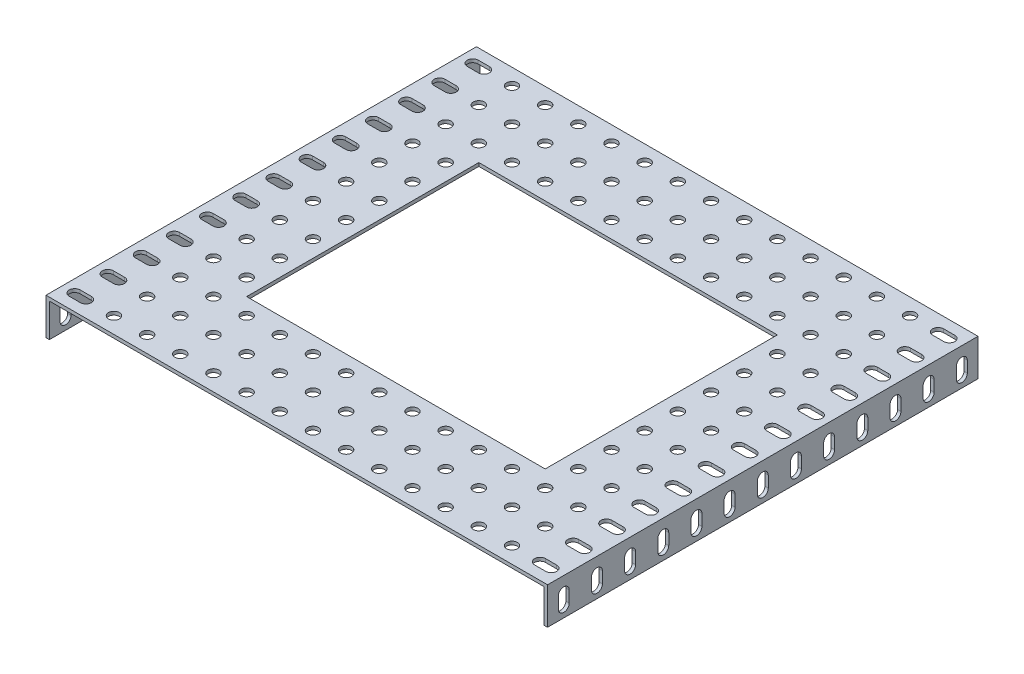
SolidWorks part; units mm, degrees
ref_plane "Front Plane" through (0, 0, 0) normal (0, 0, 1) x (1, 0, 0)
ref_plane "Top Plane" through (0, 0, 0) normal (0, 1, 0) x (1, 0, 0)
ref_plane "Right Plane" through (0, 0, 0) normal (1, 0, 0) x (0, 0, -1)
sketch "Sketch1" plane through (0, 0, 0) normal (0, 1, 0) x (1, 0, 0)
  line L0 (0, -76.56) -> (0, 76.56) construction
  line L1 (-91.66, 76.56) -> (-87.36, 76.56) construction
  line L2 (-91.66, 78.67) -> (-87.36, 78.67)
  line L3 (-91.66, 74.45) -> (-87.36, 74.45)
  line L4 (-91.66, 63.8) -> (-87.36, 63.8) construction
  line L5 (-91.66, 65.91) -> (-87.36, 65.91)
  line L6 (-91.66, 61.69) -> (-87.36, 61.69)
  line L7 (-91.66, 51.04) -> (-87.36, 51.04) construction
  line L8 (-91.66, 53.15) -> (-87.36, 53.15)
  line L9 (-91.66, 48.93) -> (-87.36, 48.93)
  line L10 (-91.66, 38.28) -> (-87.36, 38.28) construction
  line L11 (-91.66, 40.39) -> (-87.36, 40.39)
  line L12 (-91.66, 36.17) -> (-87.36, 36.17)
  line L13 (-91.66, 25.52) -> (-87.36, 25.52) construction
  line L14 (-91.66, 27.63) -> (-87.36, 27.63)
  line L15 (-91.66, 23.41) -> (-87.36, 23.41)
  line L16 (-91.66, 12.76) -> (-87.36, 12.76) construction
  line L17 (-91.66, 14.87) -> (-87.36, 14.87)
  line L18 (-91.66, 10.65) -> (-87.36, 10.65)
  line L19 (-91.66, 0) -> (-87.36, 0) construction
  line L20 (-91.66, 2.11) -> (-87.36, 2.11)
  line L21 (-91.66, -2.11) -> (-87.36, -2.11)
  line L22 (-91.66, -12.76) -> (-87.36, -12.76) construction
  line L23 (-91.66, -10.65) -> (-87.36, -10.65)
  line L24 (-91.66, -14.87) -> (-87.36, -14.87)
  line L25 (-91.66, -25.52) -> (-87.36, -25.52) construction
  line L26 (-91.66, -23.41) -> (-87.36, -23.41)
  line L27 (-91.66, -27.63) -> (-87.36, -27.63)
  line L28 (-91.66, -38.28) -> (-87.36, -38.28) construction
  line L29 (-91.66, -36.17) -> (-87.36, -36.17)
  line L30 (-91.66, -40.39) -> (-87.36, -40.39)
  line L31 (-91.66, -51.04) -> (-87.36, -51.04) construction
  line L32 (-91.66, -48.93) -> (-87.36, -48.93)
  line L33 (-91.66, -53.15) -> (-87.36, -53.15)
  line L34 (-91.66, -63.8) -> (-87.36, -63.8) construction
  line L35 (-91.66, -61.69) -> (-87.36, -61.69)
  line L36 (-91.66, -65.91) -> (-87.36, -65.91)
  line L37 (-91.66, -76.56) -> (-87.36, -76.56) construction
  line L38 (-91.66, -74.45) -> (-87.36, -74.45)
  line L39 (-91.66, -78.67) -> (-87.36, -78.67)
  line L40 (91.66, 76.56) -> (87.36, 76.56) construction
  line L41 (91.66, 78.67) -> (87.36, 78.67)
  line L42 (91.66, 74.45) -> (87.36, 74.45)
  line L43 (91.66, 63.8) -> (87.36, 63.8) construction
  line L44 (91.66, 65.91) -> (87.36, 65.91)
  line L45 (91.66, 61.69) -> (87.36, 61.69)
  line L46 (91.66, 51.04) -> (87.36, 51.04) construction
  line L47 (91.66, 53.15) -> (87.36, 53.15)
  line L48 (91.66, 48.93) -> (87.36, 48.93)
  line L49 (91.66, 38.28) -> (87.36, 38.28) construction
  line L50 (91.66, 40.39) -> (87.36, 40.39)
  line L51 (91.66, 36.17) -> (87.36, 36.17)
  line L52 (91.66, 25.52) -> (87.36, 25.52) construction
  line L53 (91.66, 27.63) -> (87.36, 27.63)
  line L54 (91.66, 23.41) -> (87.36, 23.41)
  line L55 (91.66, 12.76) -> (87.36, 12.76) construction
  line L56 (91.66, 14.87) -> (87.36, 14.87)
  line L57 (91.66, 10.65) -> (87.36, 10.65)
  line L58 (91.66, 0) -> (87.36, 0) construction
  line L59 (91.66, 2.11) -> (87.36, 2.11)
  line L60 (91.66, -2.11) -> (87.36, -2.11)
  line L61 (91.66, -12.76) -> (87.36, -12.76) construction
  line L62 (91.66, -10.65) -> (87.36, -10.65)
  line L63 (91.66, -14.87) -> (87.36, -14.87)
  line L64 (91.66, -25.52) -> (87.36, -25.52) construction
  line L65 (91.66, -23.41) -> (87.36, -23.41)
  line L66 (91.66, -27.63) -> (87.36, -27.63)
  line L67 (91.66, -38.28) -> (87.36, -38.28) construction
  line L68 (91.66, -36.17) -> (87.36, -36.17)
  line L69 (91.66, -40.39) -> (87.36, -40.39)
  line L70 (91.66, -51.04) -> (87.36, -51.04) construction
  line L71 (91.66, -48.93) -> (87.36, -48.93)
  line L72 (91.66, -53.15) -> (87.36, -53.15)
  line L73 (91.66, -63.8) -> (87.36, -63.8) construction
  line L74 (91.66, -61.69) -> (87.36, -61.69)
  line L75 (91.66, -65.91) -> (87.36, -65.91)
  line L76 (91.66, -76.56) -> (87.36, -76.56) construction
  line L77 (91.66, -74.45) -> (87.36, -74.45)
  line L78 (91.66, -78.67) -> (87.36, -78.67)
  line L80 (-93.77, 51.04) -> (-96.47, 51.04) construction
  line L81 (-96.47, 51.04) -> (-96.47, 82.79) construction
  line L83 (91.66, -78.67) -> (91.66, -82.79) construction
  line L84 (91.66, -82.79) -> (96.47, -82.79) construction
  line L86 (-96.47, 82.79) -> (96.47, 82.79)
  line L87 (-96.47, 82.79) -> (-96.47, -82.79)
  line L88 (-96.47, -82.79) -> (96.47, -82.79)
  line L89 (96.47, 82.79) -> (96.47, -82.79)
  circle A0 centre (-76.56, -76.56) radius 2.11
  circle A1 centre (-63.8, -76.56) radius 2.11
  circle A2 centre (-51.04, -76.56) radius 2.11
  circle A3 centre (-38.28, -76.56) radius 2.11
  circle A4 centre (-25.52, -76.56) radius 2.11
  circle A5 centre (-12.76, -76.56) radius 2.11
  circle A6 centre (0, -76.56) radius 2.11
  circle A7 centre (12.76, -76.56) radius 2.11
  circle A8 centre (25.52, -76.56) radius 2.11
  circle A9 centre (38.28, -76.56) radius 2.11
  circle A10 centre (51.04, -76.56) radius 2.11
  circle A11 centre (63.8, -76.56) radius 2.11
  circle A12 centre (76.56, -76.56) radius 2.11
  circle A13 centre (-63.8, -63.8) radius 2.11
  circle A14 centre (-51.04, -63.8) radius 2.11
  circle A15 centre (-38.28, -63.8) radius 2.11
  circle A16 centre (-25.52, -63.8) radius 2.11
  circle A17 centre (-12.76, -63.8) radius 2.11
  circle A18 centre (0, -63.8) radius 2.11
  circle A19 centre (12.76, -63.8) radius 2.11
  circle A20 centre (25.52, -63.8) radius 2.11
  circle A21 centre (38.28, -63.8) radius 2.11
  circle A22 centre (51.04, -63.8) radius 2.11
  circle A23 centre (63.8, -63.8) radius 2.11
  circle A24 centre (76.56, -63.8) radius 2.11
  circle A25 centre (-63.8, -51.04) radius 2.11
  circle A26 centre (-51.04, -51.04) radius 2.11
  circle A27 centre (-38.28, -51.04) radius 2.11
  circle A28 centre (-25.52, -51.04) radius 2.11
  circle A29 centre (-12.76, -51.04) radius 2.11
  circle A30 centre (0, -51.04) radius 2.11
  circle A31 centre (12.76, -51.04) radius 2.11
  circle A32 centre (25.52, -51.04) radius 2.11
  circle A33 centre (38.28, -51.04) radius 2.11
  circle A34 centre (51.04, -51.04) radius 2.11
  circle A35 centre (63.8, -51.04) radius 2.11
  circle A36 centre (76.56, -51.04) radius 2.11
  circle A37 centre (-63.8, -38.28) radius 2.11
  circle A38 centre (-51.04, -38.28) radius 2.11
  circle A39 centre (-38.28, -38.28) radius 2.11
  circle A40 centre (-25.52, -38.28) radius 2.11
  circle A41 centre (-12.76, -38.28) radius 2.11
  circle A42 centre (0, -38.28) radius 2.11
  circle A43 centre (12.76, -38.28) radius 2.11
  circle A44 centre (25.52, -38.28) radius 2.11
  circle A45 centre (38.28, -38.28) radius 2.11
  circle A46 centre (51.04, -38.28) radius 2.11
  circle A47 centre (63.8, -38.28) radius 2.11
  circle A48 centre (76.56, -38.28) radius 2.11
  circle A49 centre (-63.8, -25.52) radius 2.11
  circle A50 centre (-51.04, -25.52) radius 2.11
  circle A51 centre (-38.28, -25.52) radius 2.11
  circle A52 centre (-25.52, -25.52) radius 2.11
  circle A53 centre (-12.76, -25.52) radius 2.11
  circle A54 centre (0, -25.52) radius 2.11
  circle A55 centre (12.76, -25.52) radius 2.11
  circle A56 centre (25.52, -25.52) radius 2.11
  circle A57 centre (38.28, -25.52) radius 2.11
  circle A58 centre (51.04, -25.52) radius 2.11
  circle A59 centre (63.8, -25.52) radius 2.11
  circle A60 centre (76.56, -25.52) radius 2.11
  circle A61 centre (-63.8, -12.76) radius 2.11
  circle A62 centre (-51.04, -12.76) radius 2.11
  circle A63 centre (-38.28, -12.76) radius 2.11
  circle A64 centre (-25.52, -12.76) radius 2.11
  circle A65 centre (-12.76, -12.76) radius 2.11
  circle A66 centre (0, -12.76) radius 2.11
  circle A67 centre (12.76, -12.76) radius 2.11
  circle A68 centre (25.52, -12.76) radius 2.11
  circle A69 centre (38.28, -12.76) radius 2.11
  circle A70 centre (51.04, -12.76) radius 2.11
  circle A71 centre (63.8, -12.76) radius 2.11
  circle A72 centre (76.56, -12.76) radius 2.11
  circle A73 centre (-63.8, 0) radius 2.11
  circle A74 centre (-51.04, 0) radius 2.11
  circle A75 centre (-38.28, 0) radius 2.11
  circle A76 centre (-25.52, 0) radius 2.11
  circle A77 centre (-12.76, 0) radius 2.11
  circle A78 centre (0, 0) radius 2.11
  circle A79 centre (12.76, 0) radius 2.11
  circle A80 centre (25.52, 0) radius 2.11
  circle A81 centre (38.28, 0) radius 2.11
  circle A82 centre (51.04, 0) radius 2.11
  circle A83 centre (63.8, 0) radius 2.11
  circle A84 centre (76.56, 0) radius 2.11
  circle A85 centre (-63.8, 12.76) radius 2.11
  circle A86 centre (-51.04, 12.76) radius 2.11
  circle A87 centre (-38.28, 12.76) radius 2.11
  circle A88 centre (-25.52, 12.76) radius 2.11
  circle A89 centre (-12.76, 12.76) radius 2.11
  circle A90 centre (0, 12.76) radius 2.11
  circle A91 centre (12.76, 12.76) radius 2.11
  circle A92 centre (25.52, 12.76) radius 2.11
  circle A93 centre (38.28, 12.76) radius 2.11
  circle A94 centre (51.04, 12.76) radius 2.11
  circle A95 centre (63.8, 12.76) radius 2.11
  circle A96 centre (76.56, 12.76) radius 2.11
  circle A97 centre (-63.8, 25.52) radius 2.11
  circle A98 centre (-51.04, 25.52) radius 2.11
  circle A99 centre (-38.28, 25.52) radius 2.11
  circle A100 centre (-25.52, 25.52) radius 2.11
  circle A101 centre (-12.76, 25.52) radius 2.11
  circle A102 centre (0, 25.52) radius 2.11
  circle A103 centre (12.76, 25.52) radius 2.11
  circle A104 centre (25.52, 25.52) radius 2.11
  circle A105 centre (38.28, 25.52) radius 2.11
  circle A106 centre (51.04, 25.52) radius 2.11
  circle A107 centre (63.8, 25.52) radius 2.11
  circle A108 centre (76.56, 25.52) radius 2.11
  circle A109 centre (-63.8, 38.28) radius 2.11
  circle A110 centre (-51.04, 38.28) radius 2.11
  circle A111 centre (-38.28, 38.28) radius 2.11
  circle A112 centre (-25.52, 38.28) radius 2.11
  circle A113 centre (-12.76, 38.28) radius 2.11
  circle A114 centre (0, 38.28) radius 2.11
  circle A115 centre (12.76, 38.28) radius 2.11
  circle A116 centre (25.52, 38.28) radius 2.11
  circle A117 centre (38.28, 38.28) radius 2.11
  circle A118 centre (51.04, 38.28) radius 2.11
  circle A119 centre (63.8, 38.28) radius 2.11
  circle A120 centre (76.56, 38.28) radius 2.11
  circle A121 centre (-63.8, 51.04) radius 2.11
  circle A122 centre (-51.04, 51.04) radius 2.11
  circle A123 centre (-38.28, 51.04) radius 2.11
  circle A124 centre (-25.52, 51.04) radius 2.11
  circle A125 centre (-12.76, 51.04) radius 2.11
  circle A126 centre (0, 51.04) radius 2.11
  circle A127 centre (12.76, 51.04) radius 2.11
  circle A128 centre (25.52, 51.04) radius 2.11
  circle A129 centre (38.28, 51.04) radius 2.11
  circle A130 centre (51.04, 51.04) radius 2.11
  circle A131 centre (63.8, 51.04) radius 2.11
  circle A132 centre (76.56, 51.04) radius 2.11
  circle A133 centre (-63.8, 63.8) radius 2.11
  circle A134 centre (-51.04, 63.8) radius 2.11
  circle A135 centre (-38.28, 63.8) radius 2.11
  circle A136 centre (-25.52, 63.8) radius 2.11
  circle A137 centre (-12.76, 63.8) radius 2.11
  circle A138 centre (0, 63.8) radius 2.11
  circle A139 centre (12.76, 63.8) radius 2.11
  circle A140 centre (25.52, 63.8) radius 2.11
  circle A141 centre (38.28, 63.8) radius 2.11
  circle A142 centre (51.04, 63.8) radius 2.11
  circle A143 centre (63.8, 63.8) radius 2.11
  circle A144 centre (76.56, 63.8) radius 2.11
  circle A145 centre (-63.8, 76.56) radius 2.11
  circle A146 centre (-51.04, 76.56) radius 2.11
  circle A147 centre (-38.28, 76.56) radius 2.11
  circle A148 centre (-25.52, 76.56) radius 2.11
  circle A149 centre (-12.76, 76.56) radius 2.11
  circle A150 centre (0, 76.56) radius 2.11
  circle A151 centre (12.76, 76.56) radius 2.11
  circle A152 centre (25.52, 76.56) radius 2.11
  circle A153 centre (38.28, 76.56) radius 2.11
  circle A154 centre (51.04, 76.56) radius 2.11
  circle A155 centre (63.8, 76.56) radius 2.11
  circle A156 centre (76.56, 76.56) radius 2.11
  circle A157 centre (-76.56, -63.8) radius 2.11
  circle A158 centre (-76.56, -51.04) radius 2.11
  circle A159 centre (-76.56, -38.28) radius 2.11
  circle A160 centre (-76.56, -25.52) radius 2.11
  circle A161 centre (-76.56, -12.76) radius 2.11
  circle A162 centre (-76.56, 0) radius 2.11
  circle A163 centre (-76.56, 12.76) radius 2.11
  circle A164 centre (-76.56, 25.52) radius 2.11
  circle A165 centre (-76.56, 38.28) radius 2.11
  circle A166 centre (-76.56, 51.04) radius 2.11
  circle A167 centre (-76.56, 63.8) radius 2.11
  circle A168 centre (-76.56, 76.56) radius 2.11
  arc A169 (-91.66, 78.67) -> (-91.66, 74.45) centre (-91.66, 76.56) ccw
  arc A170 (-87.36, 74.45) -> (-87.36, 78.67) centre (-87.36, 76.56) ccw
  arc A171 (-91.66, 65.91) -> (-91.66, 61.69) centre (-91.66, 63.8) ccw
  arc A172 (-87.36, 61.69) -> (-87.36, 65.91) centre (-87.36, 63.8) ccw
  arc A173 (-91.66, 53.15) -> (-91.66, 48.93) centre (-91.66, 51.04) ccw
  arc A174 (-87.36, 48.93) -> (-87.36, 53.15) centre (-87.36, 51.04) ccw
  arc A175 (-91.66, 40.39) -> (-91.66, 36.17) centre (-91.66, 38.28) ccw
  arc A176 (-87.36, 36.17) -> (-87.36, 40.39) centre (-87.36, 38.28) ccw
  arc A177 (-91.66, 27.63) -> (-91.66, 23.41) centre (-91.66, 25.52) ccw
  arc A178 (-87.36, 23.41) -> (-87.36, 27.63) centre (-87.36, 25.52) ccw
  arc A179 (-91.66, 14.87) -> (-91.66, 10.65) centre (-91.66, 12.76) ccw
  arc A180 (-87.36, 10.65) -> (-87.36, 14.87) centre (-87.36, 12.76) ccw
  arc A181 (-91.66, 2.11) -> (-91.66, -2.11) centre (-91.66, 0) ccw
  arc A182 (-87.36, -2.11) -> (-87.36, 2.11) centre (-87.36, 0) ccw
  arc A183 (-91.66, -10.65) -> (-91.66, -14.87) centre (-91.66, -12.76) ccw
  arc A184 (-87.36, -14.87) -> (-87.36, -10.65) centre (-87.36, -12.76) ccw
  arc A185 (-91.66, -23.41) -> (-91.66, -27.63) centre (-91.66, -25.52) ccw
  arc A186 (-87.36, -27.63) -> (-87.36, -23.41) centre (-87.36, -25.52) ccw
  arc A187 (-91.66, -36.17) -> (-91.66, -40.39) centre (-91.66, -38.28) ccw
  arc A188 (-87.36, -40.39) -> (-87.36, -36.17) centre (-87.36, -38.28) ccw
  arc A189 (-91.66, -48.93) -> (-91.66, -53.15) centre (-91.66, -51.04) ccw
  arc A190 (-87.36, -53.15) -> (-87.36, -48.93) centre (-87.36, -51.04) ccw
  arc A191 (-91.66, -61.69) -> (-91.66, -65.91) centre (-91.66, -63.8) ccw
  arc A192 (-87.36, -65.91) -> (-87.36, -61.69) centre (-87.36, -63.8) ccw
  arc A193 (-91.66, -74.45) -> (-91.66, -78.67) centre (-91.66, -76.56) ccw
  arc A194 (-87.36, -78.67) -> (-87.36, -74.45) centre (-87.36, -76.56) ccw
  arc A195 (91.66, 78.67) -> (91.66, 74.45) centre (91.66, 76.56) cw
  arc A196 (87.36, 74.45) -> (87.36, 78.67) centre (87.36, 76.56) cw
  arc A197 (91.66, 65.91) -> (91.66, 61.69) centre (91.66, 63.8) cw
  arc A198 (87.36, 61.69) -> (87.36, 65.91) centre (87.36, 63.8) cw
  arc A199 (91.66, 53.15) -> (91.66, 48.93) centre (91.66, 51.04) cw
  arc A200 (87.36, 48.93) -> (87.36, 53.15) centre (87.36, 51.04) cw
  arc A201 (91.66, 40.39) -> (91.66, 36.17) centre (91.66, 38.28) cw
  arc A202 (87.36, 36.17) -> (87.36, 40.39) centre (87.36, 38.28) cw
  arc A203 (91.66, 27.63) -> (91.66, 23.41) centre (91.66, 25.52) cw
  arc A204 (87.36, 23.41) -> (87.36, 27.63) centre (87.36, 25.52) cw
  arc A205 (91.66, 14.87) -> (91.66, 10.65) centre (91.66, 12.76) cw
  arc A206 (87.36, 10.65) -> (87.36, 14.87) centre (87.36, 12.76) cw
  arc A207 (91.66, 2.11) -> (91.66, -2.11) centre (91.66, 0) cw
  arc A208 (87.36, -2.11) -> (87.36, 2.11) centre (87.36, 0) cw
  arc A209 (91.66, -10.65) -> (91.66, -14.87) centre (91.66, -12.76) cw
  arc A210 (87.36, -14.87) -> (87.36, -10.65) centre (87.36, -12.76) cw
  arc A211 (91.66, -23.41) -> (91.66, -27.63) centre (91.66, -25.52) cw
  arc A212 (87.36, -27.63) -> (87.36, -23.41) centre (87.36, -25.52) cw
  arc A213 (91.66, -36.17) -> (91.66, -40.39) centre (91.66, -38.28) cw
  arc A214 (87.36, -40.39) -> (87.36, -36.17) centre (87.36, -38.28) cw
  arc A215 (91.66, -48.93) -> (91.66, -53.15) centre (91.66, -51.04) cw
  arc A216 (87.36, -53.15) -> (87.36, -48.93) centre (87.36, -51.04) cw
  arc A217 (91.66, -61.69) -> (91.66, -65.91) centre (91.66, -63.8) cw
  arc A218 (87.36, -65.91) -> (87.36, -61.69) centre (87.36, -63.8) cw
  arc A219 (91.66, -74.45) -> (91.66, -78.67) centre (91.66, -76.56) cw
  arc A220 (87.36, -78.67) -> (87.36, -74.45) centre (87.36, -76.56) cw
  point P2 (-78.67, 76.56)
  point P3 (-89.51, 76.56)
  point P347 (-85.25, 76.56)
  point P348 (-2.11, 76.56)
  point P349 (-12.76, 74.45)
  point P350 (-89.51, 63.8)
  point P351 (-93.77, 76.56)
  point P358 (-89.51, 51.04)
  point P365 (-89.51, 38.28)
  point P372 (-89.51, 25.52)
  point P379 (-89.51, 12.76)
  point P386 (-89.51, 0)
  point P393 (-89.51, -12.76)
  point P400 (-89.51, -25.52)
  point P407 (-89.51, -38.28)
  point P414 (-89.51, -51.04)
  point P421 (-89.51, -63.8)
  point P428 (-89.51, -76.56)
  point P436 (-12.76, 65.91)
  point P437 (-10.65, 76.56)
  point P439 (89.51, 76.56)
  point P446 (89.51, 63.8)
  point P453 (89.51, 51.04)
  point P460 (89.51, 38.28)
  point P467 (89.51, 25.52)
  point P474 (89.51, 12.76)
  point P481 (89.51, 0)
  point P488 (89.51, -12.76)
  point P495 (89.51, -25.52)
  point P502 (89.51, -38.28)
  point P509 (89.51, -51.04)
  point P516 (89.51, -63.8)
  point P523 (89.51, -76.56)
  point P528 (93.77, 76.56)
  point P529 (85.25, 76.56)
  point P530 (-63.8, 78.67)
  point P533 (-93.77, 51.04)
  point P536 (93.77, -76.56)
  dimension "D1" = 4.22
  dimension "D4" = 6.58
  dimension "D5" = 4.22
  dimension "D6" = 8.52
  dimension "D7" = 8.54
  dimension "D9" = 8.54
  dimension "D10" = 8.54
  dimension "D11" = 4.12
  dimension "D12" = 2.7
  dimension "D13" = 2.7
  dimension "D14" = 4.12
  dimension "D2" = 13
  dimension "D3" = 13
  dimension "D8" = 13
extrude "Boss-Extrude1" add sketch "Sketch1" against normal blind 1.3
sketch "Sketch3" plane through (-96.47, 0, 0) normal (-1, 0, 0) x (0, 0, 1)
  line L0 (-76.56, -1.3) -> (-76.56, -14.16) construction
  line L1 (-82.79, 0) -> (82.79, 0)
  line L2 (-82.79, 0) -> (-82.79, -14.16)
  line L3 (-82.79, -14.16) -> (82.79, -14.16)
  line L4 (82.79, 0) -> (82.79, -14.16)
  line L5 (-76.56, -5.91) -> (-76.56, -10.21) construction
  line L6 (-74.45, -5.91) -> (-74.45, -10.21)
  line L7 (-78.67, -5.91) -> (-78.67, -10.21)
  line L11 (-82.79, -1.3) -> (82.79, -1.3) construction
  line L17 (-74.45, 0) -> (-78.67, 0) construction
  line L20 (-63.8, -5.91) -> (-63.8, -10.21) construction
  line L23 (-61.69, -5.91) -> (-61.69, -10.21)
  line L26 (-65.91, -5.91) -> (-65.91, -10.21)
  line L29 (-51.04, -5.91) -> (-51.04, -10.21) construction
  line L32 (-48.93, -5.91) -> (-48.93, -10.21)
  line L35 (-53.15, -5.91) -> (-53.15, -10.21)
  line L38 (-38.28, -5.91) -> (-38.28, -10.21) construction
  line L41 (-36.17, -5.91) -> (-36.17, -10.21)
  line L44 (-40.39, -5.91) -> (-40.39, -10.21)
  line L47 (-25.52, -5.91) -> (-25.52, -10.21) construction
  line L50 (-23.41, -5.91) -> (-23.41, -10.21)
  line L53 (-27.63, -5.91) -> (-27.63, -10.21)
  line L54 (-12.76, -5.91) -> (-12.76, -10.21) construction
  line L55 (-10.65, -5.91) -> (-10.65, -10.21)
  line L56 (-14.87, -5.91) -> (-14.87, -10.21)
  line L57 (0, -5.91) -> (0, -10.21) construction
  line L58 (2.11, -5.91) -> (2.11, -10.21)
  line L59 (-2.11, -5.91) -> (-2.11, -10.21)
  line L60 (12.76, -5.91) -> (12.76, -10.21) construction
  line L61 (14.87, -5.91) -> (14.87, -10.21)
  line L62 (10.65, -5.91) -> (10.65, -10.21)
  line L63 (25.52, -5.91) -> (25.52, -10.21) construction
  line L64 (27.63, -5.91) -> (27.63, -10.21)
  line L65 (23.41, -5.91) -> (23.41, -10.21)
  line L66 (38.28, -5.91) -> (38.28, -10.21) construction
  line L67 (40.39, -5.91) -> (40.39, -10.21)
  line L68 (36.17, -5.91) -> (36.17, -10.21)
  line L69 (51.04, -5.91) -> (51.04, -10.21) construction
  line L70 (53.15, -5.91) -> (53.15, -10.21)
  line L71 (48.93, -5.91) -> (48.93, -10.21)
  line L72 (63.8, -5.91) -> (63.8, -10.21) construction
  line L73 (65.91, -5.91) -> (65.91, -10.21)
  line L74 (61.69, -5.91) -> (61.69, -10.21)
  line L75 (76.56, -5.91) -> (76.56, -10.21) construction
  line L76 (78.67, -5.91) -> (78.67, -10.21)
  line L77 (74.45, -5.91) -> (74.45, -10.21)
  arc A0 (-74.45, -5.91) -> (-78.67, -5.91) centre (-76.56, -5.91) ccw
  arc A1 (-78.67, -10.21) -> (-74.45, -10.21) centre (-76.56, -10.21) ccw
  arc A32 (-61.69, -5.91) -> (-65.91, -5.91) centre (-63.8, -5.91) ccw
  arc A33 (-65.91, -10.21) -> (-61.69, -10.21) centre (-63.8, -10.21) ccw
  arc A34 (-48.93, -5.91) -> (-53.15, -5.91) centre (-51.04, -5.91) ccw
  arc A35 (-53.15, -10.21) -> (-48.93, -10.21) centre (-51.04, -10.21) ccw
  arc A36 (-36.17, -5.91) -> (-40.39, -5.91) centre (-38.28, -5.91) ccw
  arc A37 (-40.39, -10.21) -> (-36.17, -10.21) centre (-38.28, -10.21) ccw
  arc A38 (-23.41, -5.91) -> (-27.63, -5.91) centre (-25.52, -5.91) ccw
  arc A39 (-27.63, -10.21) -> (-23.41, -10.21) centre (-25.52, -10.21) ccw
  arc A40 (-10.65, -5.91) -> (-14.87, -5.91) centre (-12.76, -5.91) ccw
  arc A41 (-14.87, -10.21) -> (-10.65, -10.21) centre (-12.76, -10.21) ccw
  arc A42 (2.11, -5.91) -> (-2.11, -5.91) centre (0, -5.91) ccw
  arc A43 (-2.11, -10.21) -> (2.11, -10.21) centre (0, -10.21) ccw
  arc A44 (14.87, -5.91) -> (10.65, -5.91) centre (12.76, -5.91) ccw
  arc A45 (10.65, -10.21) -> (14.87, -10.21) centre (12.76, -10.21) ccw
  arc A46 (27.63, -5.91) -> (23.41, -5.91) centre (25.52, -5.91) ccw
  arc A47 (23.41, -10.21) -> (27.63, -10.21) centre (25.52, -10.21) ccw
  arc A48 (40.39, -5.91) -> (36.17, -5.91) centre (38.28, -5.91) ccw
  arc A49 (36.17, -10.21) -> (40.39, -10.21) centre (38.28, -10.21) ccw
  arc A50 (53.15, -5.91) -> (48.93, -5.91) centre (51.04, -5.91) ccw
  arc A51 (48.93, -10.21) -> (53.15, -10.21) centre (51.04, -10.21) ccw
  arc A52 (65.91, -5.91) -> (61.69, -5.91) centre (63.8, -5.91) ccw
  arc A53 (61.69, -10.21) -> (65.91, -10.21) centre (63.8, -10.21) ccw
  arc A54 (78.67, -5.91) -> (74.45, -5.91) centre (76.56, -5.91) ccw
  arc A55 (74.45, -10.21) -> (78.67, -10.21) centre (76.56, -10.21) ccw
  point P12 (-76.56, -8.06)
  point P18 (-76.56, -3.8)
  point P21 (-76.56, -12.32)
  point P22 (-63.8, -8.06)
  point P24 (-76.56, 0)
  point P31 (-51.04, -8.06)
  point P38 (-38.28, -8.06)
  point P45 (-25.52, -8.06)
  point P52 (-12.76, -8.06)
  point P59 (0, -8.06)
  point P66 (12.76, -8.06)
  point P73 (25.52, -8.06)
  point P80 (38.28, -8.06)
  point P87 (51.04, -8.06)
  point P94 (63.8, -8.06)
  point P101 (76.56, -8.06)
  point P109 (-78.67, -8.06)
  dimension "D1" = 14.16
  dimension "D2" = 3.8
  dimension "D3" = 8.52
  dimension "D4" = 4.22
  dimension "D6" = 8.54
  dimension "D5" = 13
extrude "Boss-Extrude2" add sketch "Sketch3" against normal blind 1.3
mirror "Mirror1" about plane through (0, 0, 0) normal (1, 0, 0) of "Boss-Extrude2"
sketch "Sketch4" plane through (0, 0, 0) normal (0, 1, 0) x (1, 0, 0)
  line L0 (-51.04, 51.04) -> (-63.8, 38.28) construction
  line L1 (51.04, 51.04) -> (63.8, 38.28) construction
  line L2 (-63.8, -38.28) -> (-51.04, -51.04) construction
  line L3 (51.04, -51.04) -> (63.8, -38.28) construction
  line L5 (-57.42, 44.66) -> (57.42, 44.66)
  line L6 (-57.42, 44.66) -> (-57.42, -44.66)
  line L7 (-57.42, -44.66) -> (57.42, -44.66)
  line L8 (57.42, 44.66) -> (57.42, -44.66)
  point P0 (-63.8, 38.28)
  point P1 (-51.04, 51.04)
  point P8 (-57.42, 44.66)
  point P9 (63.8, 38.28)
  point P10 (51.04, 51.04)
  point P12 (-51.04, -51.04)
  point P15 (-63.8, -38.28)
  point P17 (63.8, -38.28)
  point P19 (51.04, -51.04)
extrude "Cut-Extrude1" cut sketch "Sketch4" against normal blind 10 contours L7 L8 L5 L6
